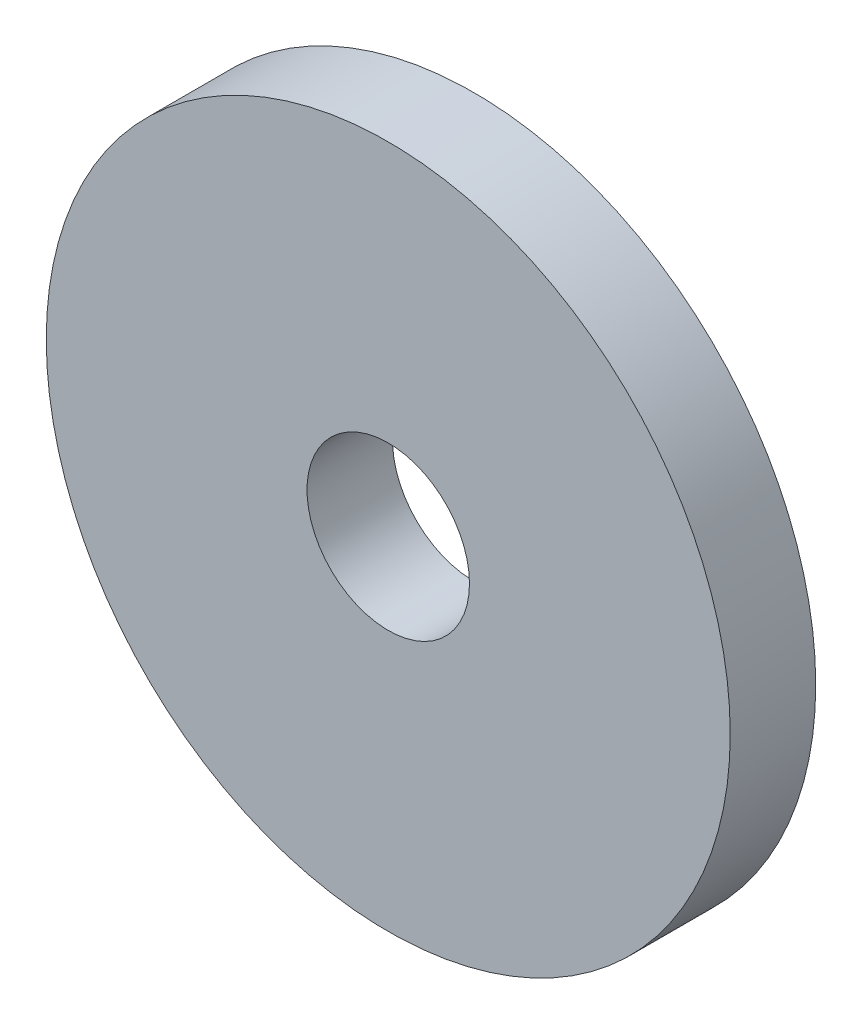
SolidWorks part; units mm, degrees
ref_plane "前视基准面" through (0, 0, 0) normal (0, 0, 1) x (1, 0, 0)
ref_plane "上视基准面" through (0, 0, 0) normal (0, 1, 0) x (1, 0, 0)
ref_plane "右视基准面" through (0, 0, 0) normal (1, 0, 0) x (0, 0, -1)
sketch "草图1" plane through (0, 0, 0) normal (0, 0, 1) x (1, 0, 0)
  circle A0 centre (150.8916, -14.8895) radius 40
extrude "凸台-拉伸4" add sketch "草图1" along normal blind 10
sketch "草图2" plane through (0, 0, 10) normal (0, 0, 1) x (1, 0, 0)
  circle A0 centre (150.8916, -14.8895) radius 9.5
extrude "切除-拉伸1" cut sketch "草图2" against normal blind 10
